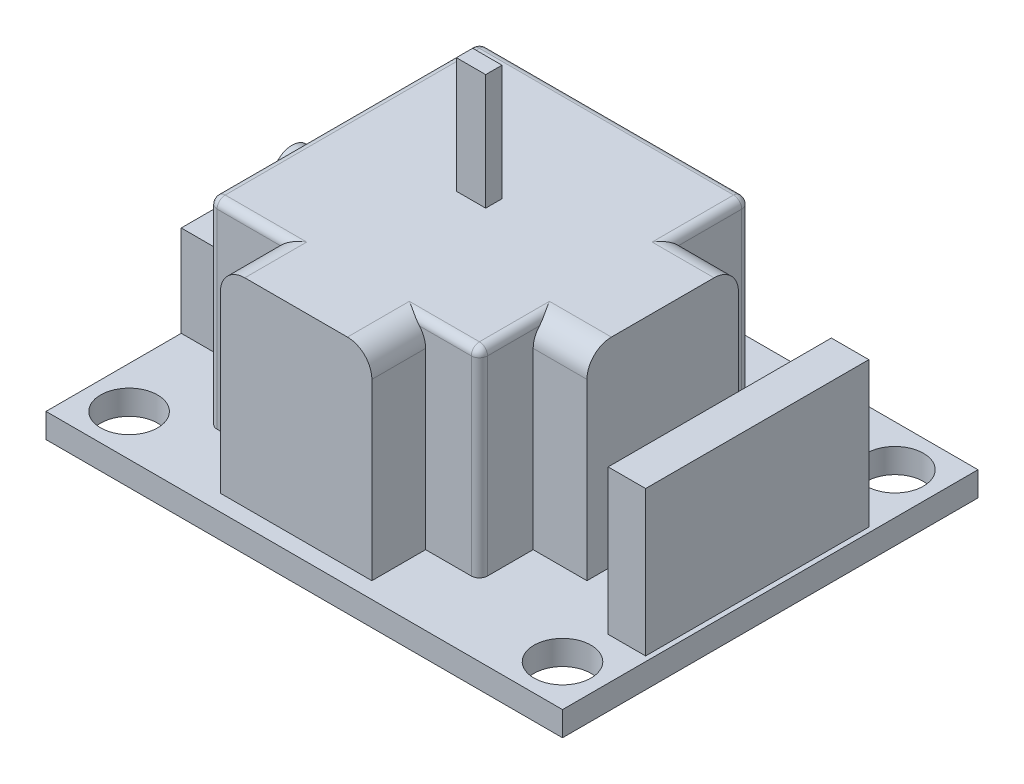
SolidWorks part; units mm, degrees
ref_plane "Front" through (0, 0, 0) normal (0, 0, 1) x (1, 0, 0)
ref_plane "Top" through (0, 0, 0) normal (0, 1, 0) x (1, 0, 0)
ref_plane "Right" through (0, 0, 0) normal (1, 0, 0) x (0, 0, -1)
sketch "Sketch1" plane through (0, 0, 0) normal (0, 1, 0) x (1, 0, 0)
  line L1 (0, 0) -> (31.7, 0)
  line L2 (0, 0) -> (0, 25.5)
  line L3 (0, 25.5) -> (31.7, 25.5)
  line L4 (31.7, 0) -> (31.7, 25.5)
  dimension "D1" = 31.7
  dimension "D2" = 25.5
extrude "Boss-Extrude1" add sketch "Sketch1" along normal blind 1.5
sketch "Sketch2" plane through (0, 1.5, 0) normal (0, 1, 0) x (1, 0, 0)
  line L0 (31.7, 25.5) -> (0, 25.5) construction
  line L1 (0, 25.5) -> (0, 0) construction
  line L2 (0, 0) -> (31.7, 0) construction
  line L3 (31.7, 0) -> (31.7, 25.5) construction
  point P0 (2.55, 22.95)
  point P1 (2.55, 2.55)
  point P2 (29.15, 2.55)
  point P3 (29.15, 22.95)
  dimension "D1" = 2.55
  dimension "D2" = 2.55
  dimension "D3" = 2.55
  dimension "D4" = 2.55
  dimension "D5" = 2.55
  dimension "D6" = 2.55
  dimension "D7" = 2.55
  dimension "D8" = 2.55
hole_wizard "Ø3.0mm Dowel Hole1" positions "3DSketch1" profile "Sketch3" hole size "Ø3.0" standard "ANSI Metric" end condition through all
sketch3d "3DSketch1"
  point P0 (2.55, 1.5, -22.95)
  point P3 (29.15, 1.5, -22.95)
  point P6 (29.15, 1.5, -2.55)
  point P9 (2.55, 1.5, -2.55)
  point P12 (39.6616, 0, -26.521)
sketch "Sketch3" plane through (2.55, 1.5, -22.95) normal (1, 0, 0) x (0, 0, 1)
  line L0 (0, 0) -> (0, 1.5)
  line L1 (0, 1.5) -> (1.75, 1.5)
  line L2 (1.75, 1.5) -> (1.75, 0)
  line L5 (1.75, 0) -> (0, 0)
  line L11 (0, -6.35) -> (0, 107.95) construction
  dimension "Thru Hole Dia." = 3.5
  dimension "Thru Hole Depth" = 1.5
sketch "Sketch4" plane through (0, 1.5, 0) normal (0, 1, 0) x (1, 0, 0)
  line L0 (31.7, 25.5) -> (0, 25.5) construction
  line L1 (5.7, 20.9) -> (22.3, 20.9)
  line L2 (5.7, 20.9) -> (5.7, 4.3)
  line L3 (5.7, 4.3) -> (9.7, 4.3)
  line L4 (22.3, 20.9) -> (22.3, 16.9)
  line L5 (31.7, 0) -> (31.7, 25.5) construction
  line L6 (0, 25.5) -> (0, 0) construction
  line L7 (0, 0) -> (31.7, 0) construction
  line L8 (19, 4.3) -> (22.3, 4.3)
  line L10 (9.7, 4.3) -> (9.7, 1)
  line L11 (9.7, 1) -> (19, 1)
  line L12 (19, 4.3) -> (19, 1)
  line L13 (22.3, 7.6) -> (25.6, 7.6)
  line L15 (22.3, 16.9) -> (25.6, 16.9)
  line L16 (25.6, 7.6) -> (25.6, 16.9)
  line L17 (22.3, 7.6) -> (22.3, 4.3)
  dimension "D1" = 4.6
  dimension "D2" = 9.4
  dimension "D3" = 5.7
  dimension "D4" = 3.3
  dimension "D5" = 4.3
  dimension "D6" = 3.3
  dimension "D7" = 9.3
  dimension "D8" = 9.3
  dimension "D9" = 3.3
  dimension "D10" = 3.3
extrude "Boss-Extrude2" add sketch "Sketch4" along normal blind 12.2
sketch "Sketch5" plane through (0, 1.5, 0) normal (0, 1, 0) x (1, 0, 0)
  line L0 (0, 0) -> (31.7, 0) construction
  line L1 (29.1, 19.1) -> (31.4, 19.1)
  line L2 (29.1, 19.1) -> (29.1, 5.4)
  line L3 (29.1, 5.4) -> (31.4, 5.4)
  line L4 (31.4, 19.1) -> (31.4, 5.4)
  line L5 (31.7, 0) -> (31.7, 25.5) construction
  dimension "D1" = 13.7
  dimension "D2" = 2.3
  dimension "D3" = 5.4
  dimension "D4" = 0.3
extrude "Boss-Extrude3" add sketch "Sketch5" along normal blind 8.9
sketch "Sketch6" plane through (0, 1.5, 0) normal (0, 1, 0) x (1, 0, 0)
  line L0 (31.7, 25.5) -> (0, 25.5) construction
  line L1 (5.7, 17.6) -> (0, 17.6)
  line L2 (5.7, 17.6) -> (5.7, 8.3)
  line L3 (5.7, 8.3) -> (0, 8.3)
  line L4 (0, 17.6) -> (0, 8.3)
  line L5 (5.7, 20.9) -> (5.7, 4.3) construction
  line L6 (0, 25.5) -> (0, 0) construction
  point P8 (0, 0)
  point P9 (0, 0)
  dimension "D1" = 9.3
  dimension "D2" = 7.9
extrude "Boss-Extrude4" add sketch "Sketch6" along normal blind 5.6
sketch "Sketch7" plane through (5.7, 0, 0) normal (-1, 0, 0) x (0, 0, 1)
  line L0 (-20.9, 13.7) -> (-4.3, 13.7) construction
  circle A0 centre (-12.6, 9.4) radius 1.2
  dimension "D1" = 2.4
  dimension "D2" = 4.3
extrude "Boss-Extrude5" add sketch "Sketch7" along normal blind 3.2
fillet "Fillet2" radius 1.5 4 edges at (23.95, 13.7, -16.9) (23.95, 13.7, -7.6) (9.7, 13.7, -2.65) (19, 13.7, -2.65)
fillet "Fillet1" radius 0.5 10 edges at (22.3, 7.6, -20.9) (22.3, 7.6, -4.3) (22.3, 13.7, -18.15) (22.3, 13.7, -6.7) (19.9, 13.7, -4.3) (8.45, 13.7, -4.3) (5.7, 7.6, -20.9) (5.7, 7.6, -4.3) (14, 13.7, -20.9) (5.7, 13.7, -12.6)
sketch "Sketch8" plane through (0, 13.7, 0) normal (0, 1, 0) x (1, 0, 0)
  line L1 (13.0911, 12.0937) -> (14.8911, 12.0937)
  line L2 (13.0911, 12.0937) -> (13.0911, 13.0937)
  line L3 (13.0911, 13.0937) -> (14.8911, 13.0937)
  line L4 (14.8911, 12.0937) -> (14.8911, 13.0937)
  line L5 (21.8, 4.8) -> (6.2, 20.4) construction
  line L6 (21.8, 20.4) -> (6.2, 4.8) construction
  line L7 (13.0911, 12.0937) -> (14.8911, 13.0937) construction
  line L9 (14.8911, 12.0937) -> (13.0911, 13.0937) construction
  point P12 (14, 12.6)
  point P13 (13.9911, 12.5937)
  point P15 (13.9911, 12.5937)
  dimension "D1" = 1.8
  dimension "D2" = 1
extrude "Boss-Extrude6" add sketch "Sketch8" along normal blind 7.1
equation "\"D1@Sketch2\"=(3.5/2)+0.8"
equation "\"D2@Sketch2\"=\"D1@Sketch2\""
equation "\"D3@Sketch2\"=\"D1@Sketch2\""
equation "\"D4@Sketch2\"=\"D1@Sketch2\""
equation "\"D5@Sketch2\"=\"D1@Sketch2\""
equation "\"D6@Sketch2\"=\"D1@Sketch2\""
equation "\"D7@Sketch2\"=\"D1@Sketch2\""
equation "\"D8@Sketch2\"=\"D1@Sketch2\""
equation "\"D2@Sketch7\"=(\"D1@Sketch7\"/2)+3.1"
